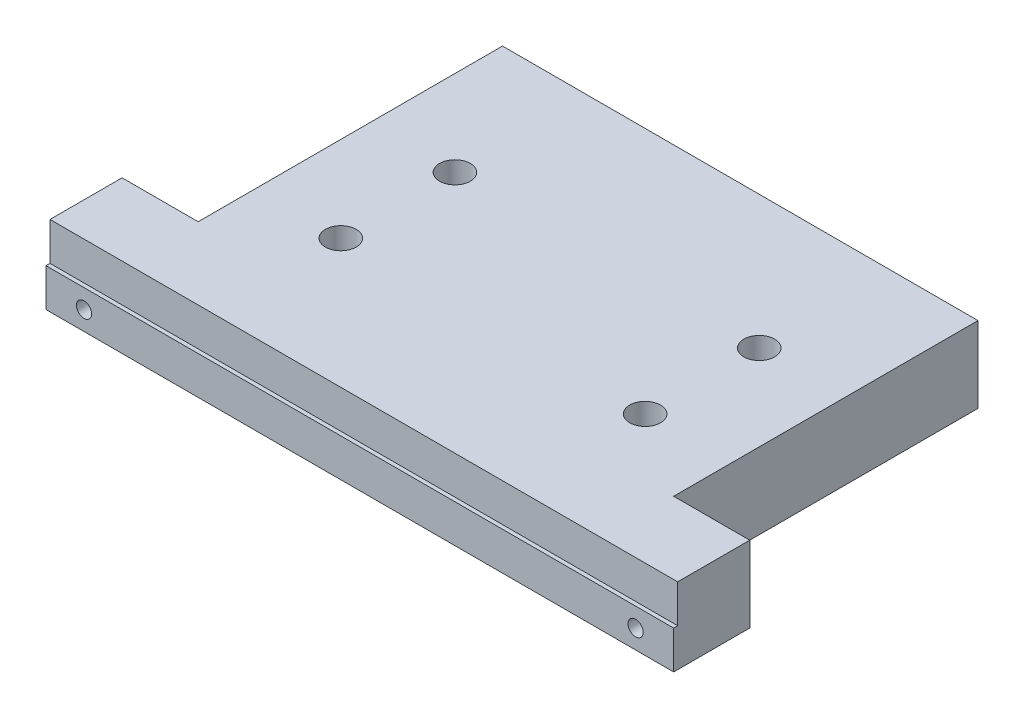
SolidWorks part; units mm, degrees
ref_plane "Front Plane" through (0, 0, 0) normal (0, 0, 1) x (1, 0, 0)
ref_plane "Top Plane" through (0, 0, 0) normal (0, 1, 0) x (1, 0, 0)
ref_plane "Right Plane" through (0, 0, 0) normal (1, 0, 0) x (0, 0, -1)
sketch "Sketch1" plane through (0, 0, 0) normal (0, 0, 1) x (1, 0, 0)
  line L0 (0, 0) -> (125, 0)
  line L1 (0, 0) -> (0, 20)
  line L2 (125, 0) -> (125, 20)
  line L3 (0, 20) -> (125, 20)
  dimension "D1" = 20
  dimension "D2" = 125
extrude "Boss-Extrude1" add sketch "Sketch1" along normal blind 100
sketch "Sketch2" plane through (0, 20, 0) normal (0, 1, 0) x (1, 0, 0)
  line L0 (22.5, -35) -> (22.5, -65) construction
  line L1 (32.5, -35) -> (32.5, -65)
  line L2 (12.5, -35) -> (12.5, -65)
  line L3 (102.5, -35) -> (102.5, -65) construction
  line L6 (125, -100) -> (0, -100) construction
  line L7 (92.5, -35) -> (92.5, -65)
  line L8 (112.5, -35) -> (112.5, -65)
  line L9 (62.5, 0) -> (62.5, -100) construction
  line L10 (125, 0) -> (0, 0) construction
  arc A0 (32.5, -35) -> (12.5, -35) centre (22.5, -35) ccw
  arc A1 (12.5, -65) -> (32.5, -65) centre (22.5, -65) ccw
  arc A4 (92.5, -35) -> (112.5, -35) centre (102.5, -35) cw
  arc A5 (112.5, -65) -> (92.5, -65) centre (102.5, -65) cw
  point P2 (22.5, -50)
  point P9 (102.5, -50)
  dimension "D1" = 50
  dimension "D3" = 30
  dimension "D5" = 20
  dimension "D7" = 40
sketch "Sketch8" plane through (0, 0, 0) normal (-1, 0, 0) x (0, 0, 1)
  line L0 (0, 20) -> (100, 20) construction
  line L1 (80, 20) -> (100, 20)
  line L2 (80, 20) -> (80, 0)
  line L3 (80, 0) -> (100, 0)
  line L4 (100, 20) -> (100, 0)
  dimension "D1" = 20
extrude "Boss-Extrude2" add sketch "Sketch8" along normal blind 20
sketch "Sketch11" plane through (0, 20, 0) normal (0, 1, 0) x (1, 0, 0)
  line L0 (12.5, -35) -> (12.5, -65) construction
  line L1 (62.5, -100) -> (62.5, 0) construction
  circle A0 centre (22.5, -35) radius 4.05
  circle A1 centre (22.5, -65) radius 4.05
  circle A2 centre (102.5, -65) radius 4.05
  circle A3 centre (102.5, -35) radius 4.05
  dimension "D1" = 8.1
  dimension "D2" = 10
  dimension "D3" = 8.1
extrude "Cut-Extrude3" cut sketch "Sketch11" against normal blind 40
sketch "Sketch9" plane through (125, 0, 0) normal (1, 0, 0) x (0, 0, -1)
  line L1 (-100, 20) -> (-80, 20)
  line L2 (-100, 20) -> (-100, 0)
  line L3 (-100, 0) -> (-80, 0)
  line L4 (-80, 20) -> (-80, 0)
  dimension "D1" = 20
  dimension "D2" = 20
extrude "Boss-Extrude3" add sketch "Sketch9" along normal blind 20
sketch "Sketch10" plane through (0, 0, 80) normal (0, 0, -1) x (-1, 0, 0)
  line L0 (20, 20) -> (20, 0) construction
  line L1 (20, 0) -> (0, 0) construction
  line L2 (-62.5, 20) -> (-62.5, 0) construction
  line L3 (-125, 20) -> (0, 20) construction
  line L4 (0, 0) -> (-125, 0) construction
  circle A0 centre (10, 5) radius 2
  circle A1 centre (-135, 5) radius 2
  dimension "D1" = 10
  dimension "D2" = 5
  dimension "D3" = 4
extrude "Cut-Extrude2" cut sketch "Sketch10" against normal blind 20
sketch "Esquisse2" plane through (0, 20, 0) normal (0, 1, 0) x (1, 0, 0)
  line L0 (145, -80) -> (145, -100) construction
  line L1 (-20, -100) -> (145, -100)
  line L2 (-20, -100) -> (-20, -98.95)
  line L3 (-20, -98.95) -> (145, -98.95)
  line L4 (145, -100) -> (145, -98.95)
  dimension "D1" = 1.05
extrude "Enlèv. mat.-Extru.1" cut sketch "Esquisse2" against normal blind 10
